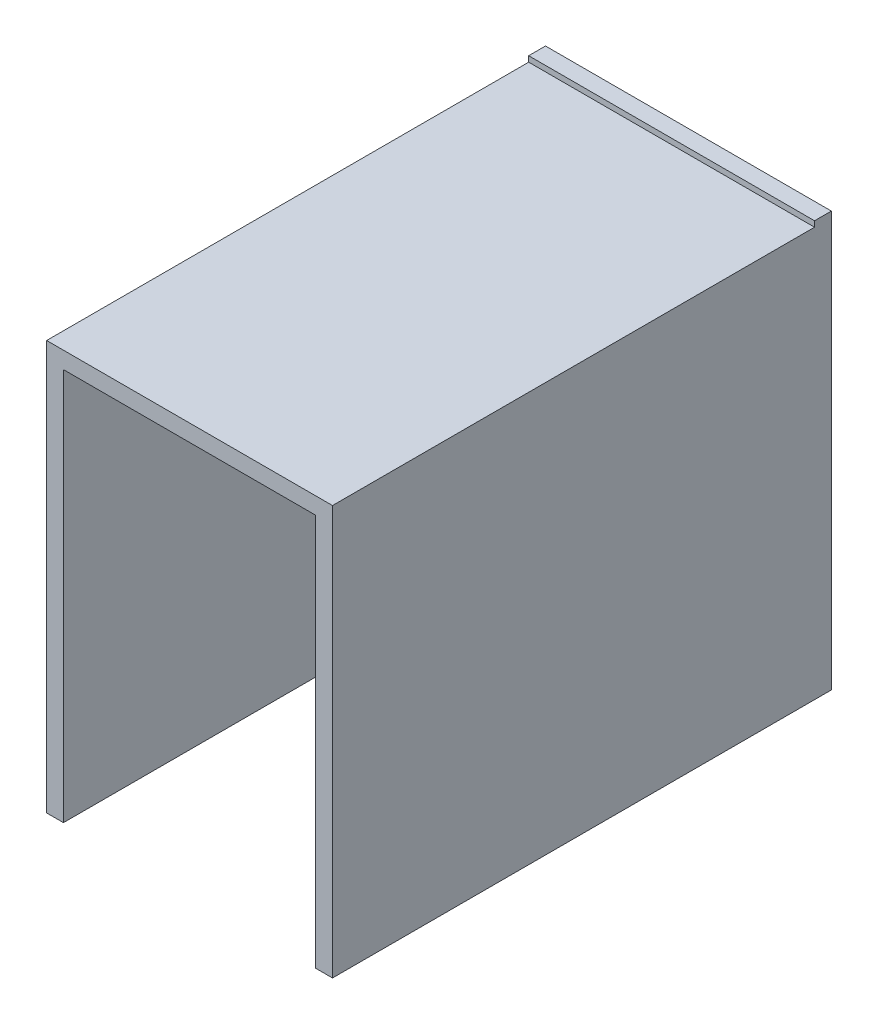
SolidWorks part; units mm, degrees
ref_plane "Front Plane" through (0, 0, 0) normal (0, 0, 1) x (1, 0, 0)
ref_plane "Top Plane" through (0, 0, 0) normal (0, 1, 0) x (1, 0, 0)
ref_plane "Right Plane" through (0, 0, 0) normal (1, 0, 0) x (0, 0, -1)
sketch "Sketch1" plane through (0, 0, 0) normal (0, 0, 1) x (1, 0, 0)
  line L14 (8, -2.8723) -> (8, -14.2558)
  line L15 (8, -14.2558) -> (9.25, -14.2558)
  line L16 (-8, -2.8723) -> (-8, -14.2558)
  line L17 (9.25, -14.2558) -> (9.25, -3.4911)
  line L18 (-9.25, -3.4911) -> (-9.25, -14.2558)
  line L19 (-9.25, -14.2558) -> (-8, -14.2558)
  arc A3 (9.25, -3.4911) -> (-9.25, -3.4911) centre (0, 0.0552) ccw
  arc A5 (8, -2.8723) -> (-8, -2.8723) centre (0, 0) ccw
extrude "Boss-Extrude1" add sketch "Sketch1" along normal blind 9
sketch "Sketch3" plane through (0, 0, 0) normal (0, 0, 1) x (1, 0, 0)
  line L1 (-11.25, 11.2) -> (11.25, 11.2)
  line L2 (-11.25, 11.2) -> (-11.25, -23.8)
  line L3 (-11.25, -23.8) -> (11.25, -23.8)
  line L4 (11.25, 11.2) -> (11.25, -23.8)
  arc A1 (8, -2.8723) -> (-8, -2.8723) centre (0, 0) ccw construction
  point P0 (0, 0)
  point P9 (0, 8.5)
  dimension "D1" = 2.7
  dimension "D2" = 11.25
  dimension "D3" = 11.25
  dimension "D4" = 35
extrude "Boss-Extrude2" add sketch "Sketch3" against normal blind 1.5
sketch "Sketch9" plane through (0, 0, 0) normal (0, 0, 1) x (1, 0, 0)
  line L1 (-12.75, 12.7) -> (12.75, 12.7)
  line L5 (-11.25, 11.2) -> (11.25, 11.2)
  line L8 (11.25, 11.2) -> (11.25, -23.8)
  line L15 (-12.75, 12.7) -> (-12.75, -23.8)
  line L16 (-12.75, -23.8) -> (-11.25, -23.8)
  line L17 (-11.25, -23.8) -> (-11.25, 11.2)
  line L18 (12.75, 12.7) -> (12.75, -23.8)
  line L19 (12.75, -23.8) -> (11.25, -23.8)
  dimension "D1" = 1.5
  dimension "D2" = 1.5
  dimension "D3" = 1.5
extrude "Boss-Extrude5" add sketch "Sketch9" along normal blind 43 separate body
sketch "Sketch10" plane through (0, 0, 0) normal (0, 0, 1) x (1, 0, 0)
  line L1 (-12.75, 13.2) -> (12.75, 13.2)
  line L5 (11.25, 11.2) -> (-11.25, 11.2)
  line L8 (-12.75, -23.8) -> (-12.75, 13.2)
  line L9 (-11.25, 11.2) -> (-11.25, -23.8)
  line L10 (-11.25, -23.8) -> (-12.75, -23.8)
  line L11 (11.25, -23.8) -> (11.25, 11.2)
  line L12 (12.75, 13.2) -> (12.75, -23.8)
  line L13 (12.75, -23.8) -> (11.25, -23.8)
extrude "Boss-Extrude6" add sketch "Sketch10" against normal blind 1.5
